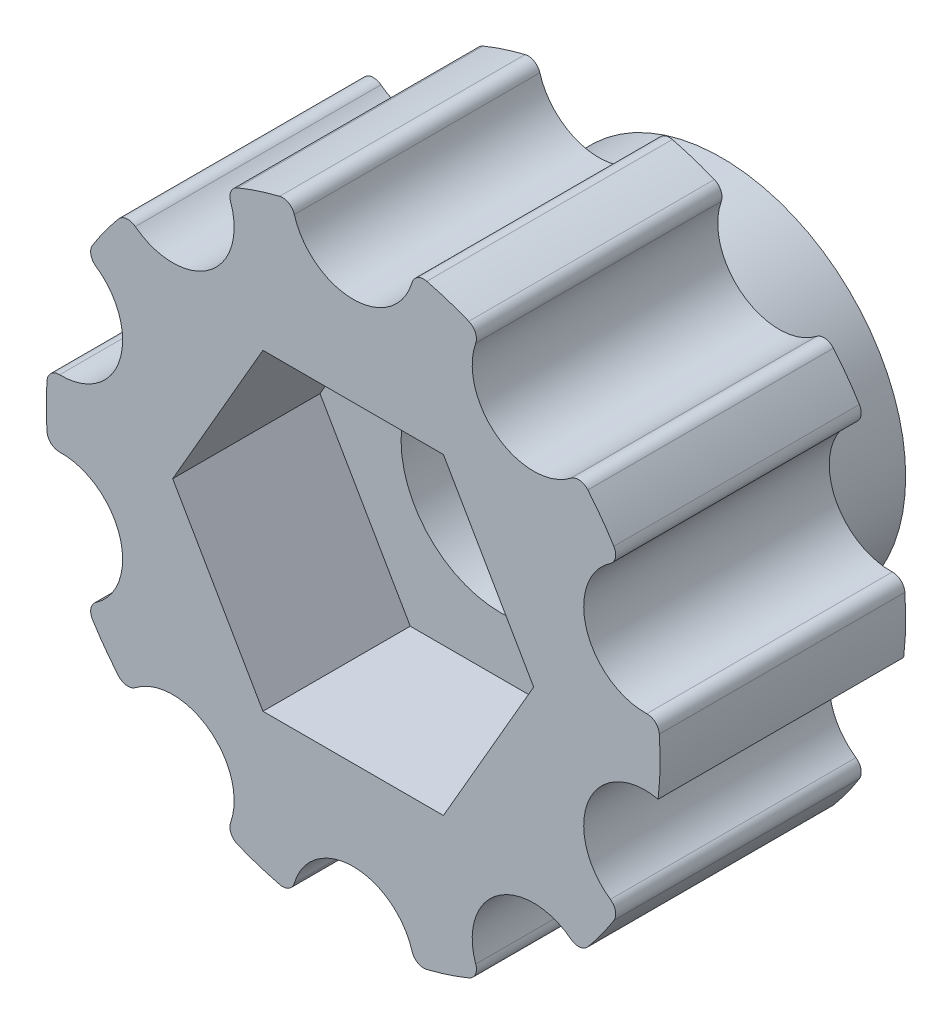
SolidWorks part; units mm, degrees
ref_plane "Front Plane" through (0, 0, 0) normal (0, 0, 1) x (1, 0, 0)
ref_plane "Top Plane" through (0, 0, 0) normal (0, 1, 0) x (1, 0, 0)
ref_plane "Right Plane" through (0, 0, 0) normal (1, 0, 0) x (0, 0, -1)
sketch "Sketch1" plane through (0, 0, 0) normal (0, 0, 1) x (1, 0, 0)
  circle A0 centre (0, 0) radius 12.5
  dimension "D1" = 25
extrude "Boss-Extrude1" add sketch "Sketch1" along normal blind 10
sketch "Sketch2" plane through (0, 0, 0) normal (0, 0, -1) x (-1, 0, 0)
  circle A0 centre (0, 0) radius 7.5
  dimension "D1" = 15
extrude "Boss-Extrude2" add sketch "Sketch2" along normal blind 5
sketch "Sketch3" plane through (0, 0, -5) normal (0, 0, -1) x (-1, 0, 0)
  circle A0 centre (0, 0) radius 4.05
  dimension "D1" = 8.1
extrude "Cut-Extrude1" cut sketch "Sketch3" against normal through all
sketch "Sketch4" plane through (0, 0, 10) normal (0, 0, 1) x (1, 0, 0)
  line L0 (0, 0) -> (5, 0) construction
  line L1 (0, 0) -> (3.675, 6.3653) construction
  line L2 (3.675, 6.3653) -> (-3.675, 6.3653)
  line L3 (-3.675, 6.3653) -> (-7.35, 0)
  line L4 (-7.35, 0) -> (-3.675, -6.3653)
  line L5 (-3.675, -6.3653) -> (3.675, -6.3653)
  line L6 (3.675, -6.3653) -> (7.35, 0)
  line L7 (7.35, 0) -> (3.675, 6.3653)
  circle A0 centre (0, 0) radius 7.35 construction
  dimension "D2" = 14.7
  dimension "D1" = 5
  dimension "D3" = 60
extrude "Cut-Extrude2" cut sketch "Sketch4" against normal blind 6
sketch "Sketch5" plane through (0, 0, 10) normal (0, 0, 1) x (1, 0, 0)
  line L0 (0, 0) -> (0, 12.5) construction
  line L1 (0, 0) -> (7.3473, 10.1127) construction
  circle A0 centre (0, 0) radius 12.5 construction
  circle A1 centre (0, 12.5) radius 2.5
  circle A2 centre (7.3473, 10.1127) radius 2.5
  circle A3 centre (11.8882, 3.8627) radius 2.5
  circle A4 centre (11.8882, -3.8627) radius 2.5
  circle A5 centre (7.3473, -10.1127) radius 2.5
  circle A6 centre (0, -12.5) radius 2.5
  circle A7 centre (-7.3473, -10.1127) radius 2.5
  circle A8 centre (-11.8882, -3.8627) radius 2.5
  circle A9 centre (-11.8882, 3.8627) radius 2.5
  circle A10 centre (-7.3473, 10.1127) radius 2.5
  point P28 (0, 0)
  dimension "D1" = 5
  dimension "D4" = 7.3473
  dimension "D3" = 36
  dimension "D2" = 10
extrude "Cut-Extrude3" cut sketch "Sketch5" against normal through all
fillet "Fillet1" radius 0.5 19 edges at (-9.2128, 8.4484, 5) (-5.188, 11.3726, 5) (-12.4191, 1.4197, 5) (-10.8818, 6.1512, 5) (-10.8818, -6.1512, 5) (-12.4191, -1.4197, 5) (-5.188, -11.3726, 5) (-9.2128, -8.4484, 5) (2.4875, -12.25, 5) (-2.4875, -12.25, 5) (9.2128, -8.4484, 5) (5.188, -11.3726, 5) (10.8818, -6.1512, 5) (10.8818, 6.1512, 5) (12.4191, 1.4197, 5) (5.188, 11.3726, 5) (9.2128, 8.4484, 5) (-2.4875, 12.25, 5) (2.4875, 12.25, 5)
